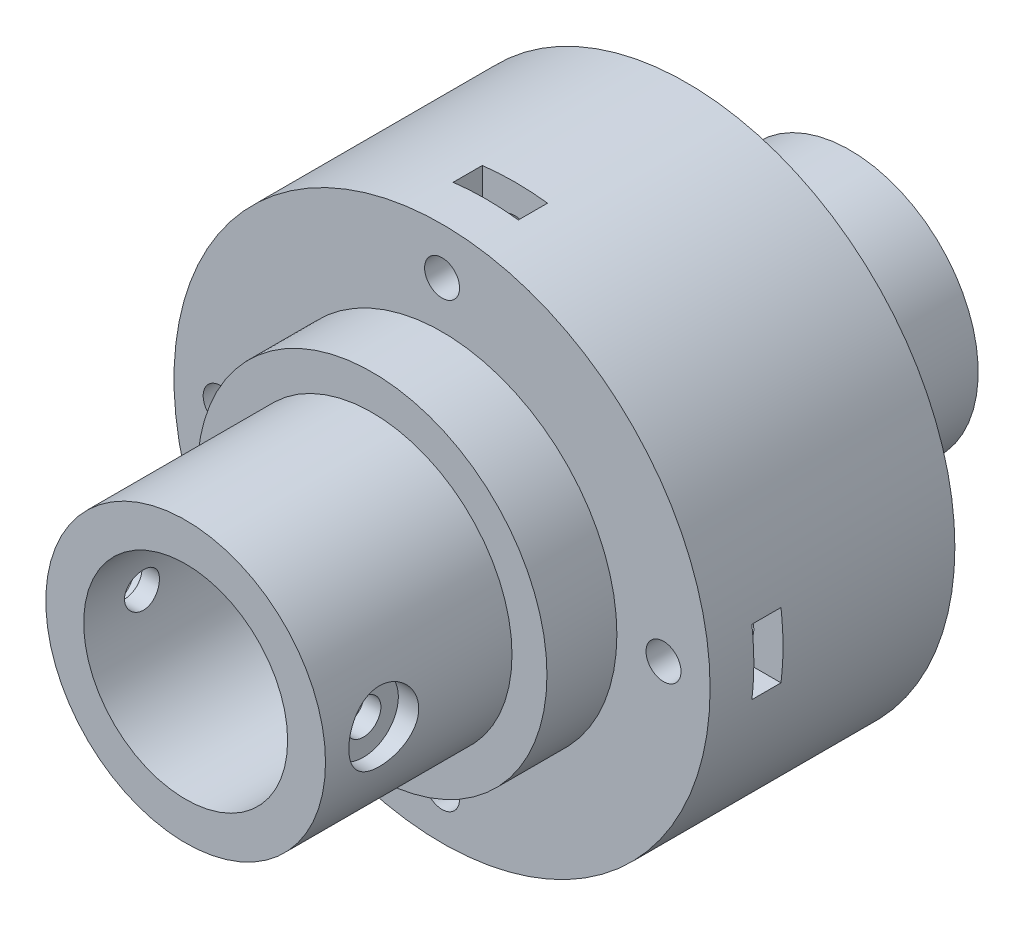
SolidWorks part; units mm, degrees
ref_plane "Front Plane" through (0, 0, 0) normal (0, 0, 1) x (1, 0, 0)
ref_plane "Top Plane" through (0, 0, 0) normal (0, 1, 0) x (1, 0, 0)
ref_plane "Right Plane" through (0, 0, 0) normal (1, 0, 0) x (0, 0, -1)
sketch "Sketch1" plane through (0, 0, 0) normal (0, 0, 1) x (1, 0, 0)
  circle A0 centre (0, 0) radius 13
  circle A1 centre (0, 0) radius 15
extrude "Boss-Extrude1" add sketch "Sketch1" along normal blind 11 and the other way blind 5
sketch "Sketch2" plane through (0, 0, 0) normal (0, 0, 1) x (1, 0, 0)
  circle A0 centre (0, 0) radius 23
  circle A1 centre (0, 0) radius 8.75
extrude "Boss-Extrude2" add sketch "Sketch2" along normal blind 5 and the other way blind 10
sketch "Sketch6" plane through (0, 0, 5) normal (0, 0, 1) x (1, 0, 0)
  circle A2 centre (0, 19) radius 1.5
  circle A3 centre (19, 0) radius 1.5
  circle A4 centre (0, -19) radius 1.5
  circle A5 centre (-19, 0) radius 1.5
  point P18 (0, 0)
  dimension "D1" = 4
extrude "Cut-Extrude1" cut sketch "Sketch6" against normal blind 23
sketch "Sketch9" plane through (0, 0, 0) normal (0, 0, 1) x (1, 0, 0)
  line L0 (-2.8, 20.6166) -> (-2.8, 26.4487)
  line L1 (0, 15.7668) -> (2.8, 17.3834)
  line L2 (2.8, 17.3834) -> (2.8, 20.6166)
  line L5 (-2.8, 20.6166) -> (-2.8, 17.3834)
  line L6 (-2.8, 17.3834) -> (0, 15.7668)
  line L7 (-2.8, 26.4487) -> (2.8, 26.4487)
  line L8 (2.8, 20.6166) -> (2.8, 26.4487)
  line L9 (20.6166, 2.8) -> (26.4487, 2.8)
  line L10 (2.8, 20.6166) -> (1.4, 21.4249) [skipped]
  line L11 (-1.4, 21.4249) -> (-2.8, 20.6166) [skipped]
  line L12 (26.4487, 2.8) -> (26.4487, -2.8)
  line L13 (20.6166, -2.8) -> (26.4487, -2.8)
  line L14 (17.3834, -2.8) -> (20.6166, -2.8)
  line L15 (15.7668, 0) -> (17.3834, -2.8)
  line L16 (17.3834, 2.8) -> (15.7668, 0)
  line L17 (20.6166, 2.8) -> (17.3834, 2.8)
  line L18 (2.8, -20.6166) -> (2.8, -26.4487)
  line L19 (2.8, -26.4487) -> (-2.8, -26.4487)
  line L20 (-2.8, -20.6166) -> (-2.8, -26.4487)
  line L21 (-2.8, -17.3834) -> (-2.8, -20.6166)
  line L22 (0, -15.7668) -> (-2.8, -17.3834)
  line L23 (2.8, -17.3834) -> (0, -15.7668)
  line L24 (2.8, -20.6166) -> (2.8, -17.3834)
  line L25 (-20.6166, -2.8) -> (-26.4487, -2.8)
  line L26 (-26.4487, -2.8) -> (-26.4487, 2.8)
  line L27 (-20.6166, 2.8) -> (-26.4487, 2.8)
  line L28 (-17.3834, 2.8) -> (-20.6166, 2.8)
  line L29 (-15.7668, 0) -> (-17.3834, 2.8)
  line L30 (-17.3834, -2.8) -> (-15.7668, 0)
  line L31 (-20.6166, -2.8) -> (-17.3834, -2.8)
  arc A0 (-2.8, 19) -> (2.8, 19) centre (0, 19) ccw construction
  point P39 (0, 0)
  dimension "D1" = 4
extrude "Cut-Extrude2" cut sketch "Sketch9" against normal blind 1.25 and the other way blind 1.25
sketch "Sketch13" plane through (0, 0, 5) normal (0, 0, 1) x (1, 0, 0)
  circle A0 centre (0, 0) radius 8.75
  circle A1 centre (0, 0) radius 13
extrude "Boss-Extrude5" add sketch "Sketch13" along normal blind 6
sketch "Sketch14" plane through (0, 0, 11) normal (0, 0, 1) x (1, 0, 0)
  circle A0 centre (0, 0) radius 8.75
  circle A1 centre (0, 0) radius 12
extrude "Boss-Extrude6" add sketch "Sketch14" along normal blind 16
sketch "Sketch17" plane through (0, 0, -10) normal (0, 0, -1) x (-1, 0, 0)
  circle A0 centre (0, 0) radius 8.75
  circle A1 centre (0, 0) radius 11
extrude "Boss-Extrude7" add sketch "Sketch17" along normal blind 20
ref_plane "Plane3" through (10.25, 0, 0) normal (1, 0, 0) x (0, 0, -1)
sketch "Sketch18" plane through (0, 0, 0) normal (1, 0, 0) x (0, 0, -1)
  line L0 (-27, 0) -> (-22, 0)
  line L1 (-27, 12) -> (-27, -12) construction
  circle A0 centre (-22, 0) radius 1.5
extrude "Cut-Extrude3" cut sketch "Sketch18" against normal blind 57 and the other way blind 57
sketch "Sketch19" plane through (10.25, 0, 0) normal (1, 0, 0) x (0, 0, -1)
  circle A0 centre (-22, 0) radius 3
extrude "Cut-Extrude4" cut sketch "Sketch19" along normal blind 14
mirror "Mirror1" about plane through (0, 0, 0) normal (1, 0, 0) of "Cut-Extrude4"
sketch "Sketch20" plane through (0, 0, -10) normal (0, 0, -1) x (-1, 0, 0)
  circle A0 centre (0, 0) radius 23
  circle A1 centre (0, 0) radius 11
extrude "Boss-Extrude8" add sketch "Sketch20" along normal blind 6
